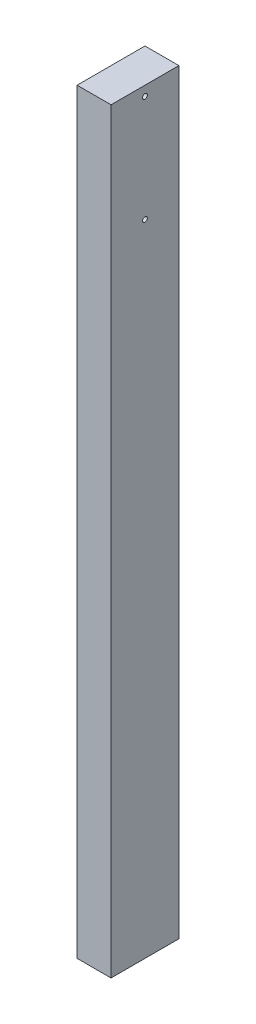
SolidWorks part; units mm, degrees
ref_plane "Front Plane" through (0, 0, 0) normal (0, 0, 1) x (1, 0, 0)
ref_plane "Top Plane" through (0, 0, 0) normal (0, 1, 0) x (1, 0, 0)
ref_plane "Right Plane" through (0, 0, 0) normal (1, 0, 0) x (0, 0, -1)
sketch "Sketch1" plane through (0, 0, 0) normal (0, 1, 0) x (1, 0, 0)
  line L1 (22.225, 44.45) -> (-22.225, 44.45)
  line L2 (22.225, 44.45) -> (22.225, -44.45)
  line L3 (22.225, -44.45) -> (-22.225, -44.45)
  line L4 (-22.225, 44.45) -> (-22.225, -44.45)
  line L5 (22.225, 44.45) -> (-22.225, -44.45) construction
  line L6 (22.225, -44.45) -> (-22.225, 44.45) construction
  point P0 (0, 0)
  dimension "D1" = 88.9
  dimension "D2" = 44.45
extrude "Boss-Extrude1" add sketch "Sketch1" along normal blind 990.6
sketch "Sketch2" plane through (-22.225, 0, 0) normal (-1, 0, 0) x (0, 0, 1)
  line L0 (-44.45, 990.6) -> (44.45, 990.6) construction
  line L1 (-44.45, 990.6) -> (-44.45, 0) construction
  circle A0 centre (0, 977.9) radius 3.175
  circle A1 centre (0, 838.2) radius 3.175
  dimension "D1" = 6.35
  dimension "D2" = 12.7
  dimension "D3" = 44.45
  dimension "D4" = 6.35
  dimension "D5" = 44.45
  dimension "D6" = 152.4
extrude "Cut-Extrude1" cut sketch "Sketch2" against normal blind 977.9
